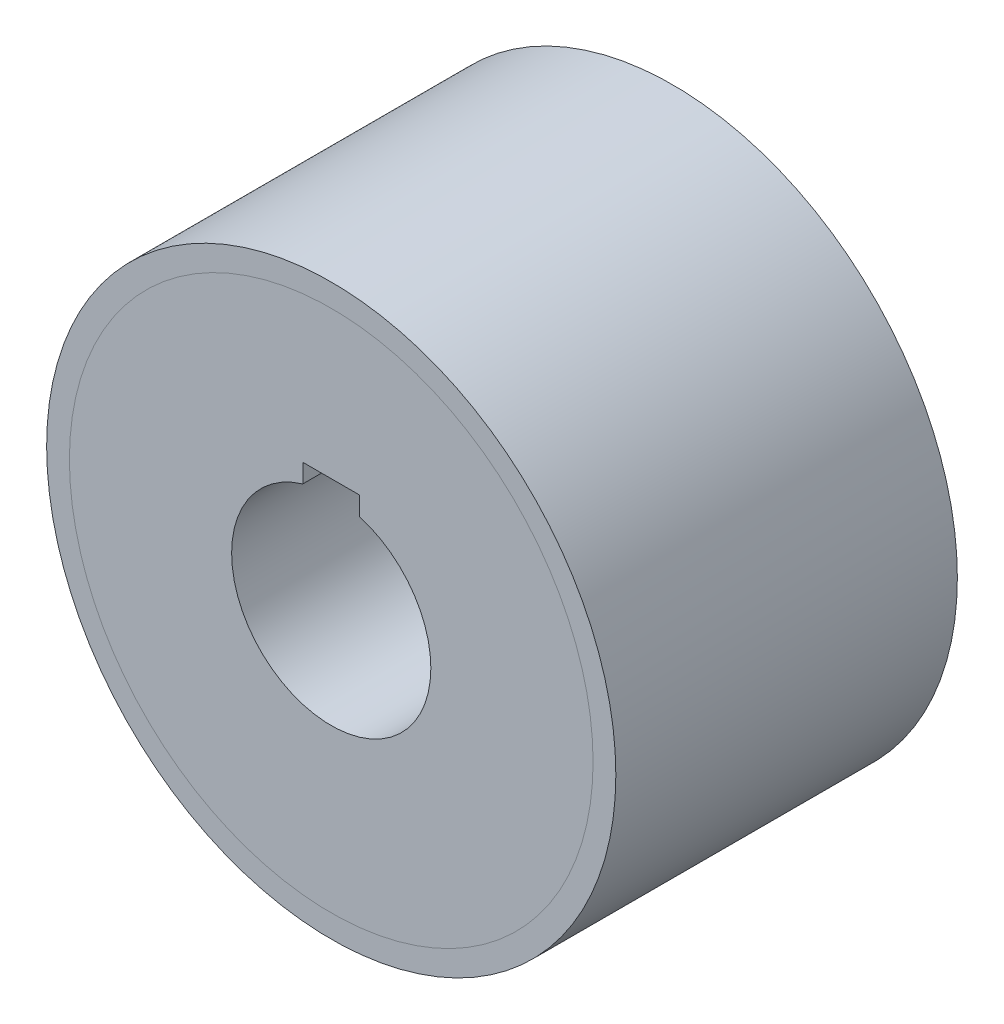
SolidWorks part; units mm, degrees
material "1.7225 (42CrMo4)"
ref_plane "Front Plane" through (0, 0, 0) normal (0, 0, 1) x (1, 0, 0)
ref_plane "Top Plane" through (0, 0, 0) normal (0, 1, 0) x (1, 0, 0)
ref_plane "Right Plane" through (0, 0, 0) normal (1, 0, 0) x (0, 0, -1)
sketch "Sketch1" plane through (0, 0, 0) normal (0, 0, 1) x (1, 0, 0)
  circle A0 centre (0, 0) radius 46
  dimension "D1" = 92
extrude "Boss-Extrude1" add sketch "Sketch1" along normal blind 60
sketch "Sketch2" plane through (0, 0, 0) normal (0, 0, -1) x (-1, 0, 0)
  circle A0 centre (0, 0) radius 17.5
  dimension "D1" = 35
extrude "Cut-Extrude1" cut sketch "Sketch2" against normal through all
sketch "Sketch3" plane through (0, 0, 0) normal (0, 0, -1) x (-1, 0, 0)
  line L0 (0, 0) -> (0, 46) construction
  line L1 (-5, 16.7705) -> (-5, 20.0705)
  line L2 (-5, 20.0705) -> (5, 20.0705)
  line L3 (5, 16.7705) -> (5, 20.0705)
  circle A0 centre (0, 0) radius 46 construction
  circle A1 centre (0, 0) radius 17.5 construction
  arc A2 (5, 16.7705) -> (-5, 16.7705) centre (0, 0) ccw
  point P12 (0, 20.0705)
  dimension "D1" = 3.3
  dimension "D2" = 10
extrude "Cut-Extrude2" cut sketch "Sketch3" against normal through all
sketch "Sketch4" plane through (0, 0, 0) normal (0, 0, -1) x (-1, 0, 0)
  circle A0 centre (0, 0) radius 46 construction
  circle A1 centre (0, 0) radius 46
  circle A2 centre (0, 0) radius 50
  dimension "D1" = 100
extrude "Boss-Extrude2" add sketch "Sketch4" against normal up to surface (60 mm away) separate body up to face at (0, 9.8529, 60)
